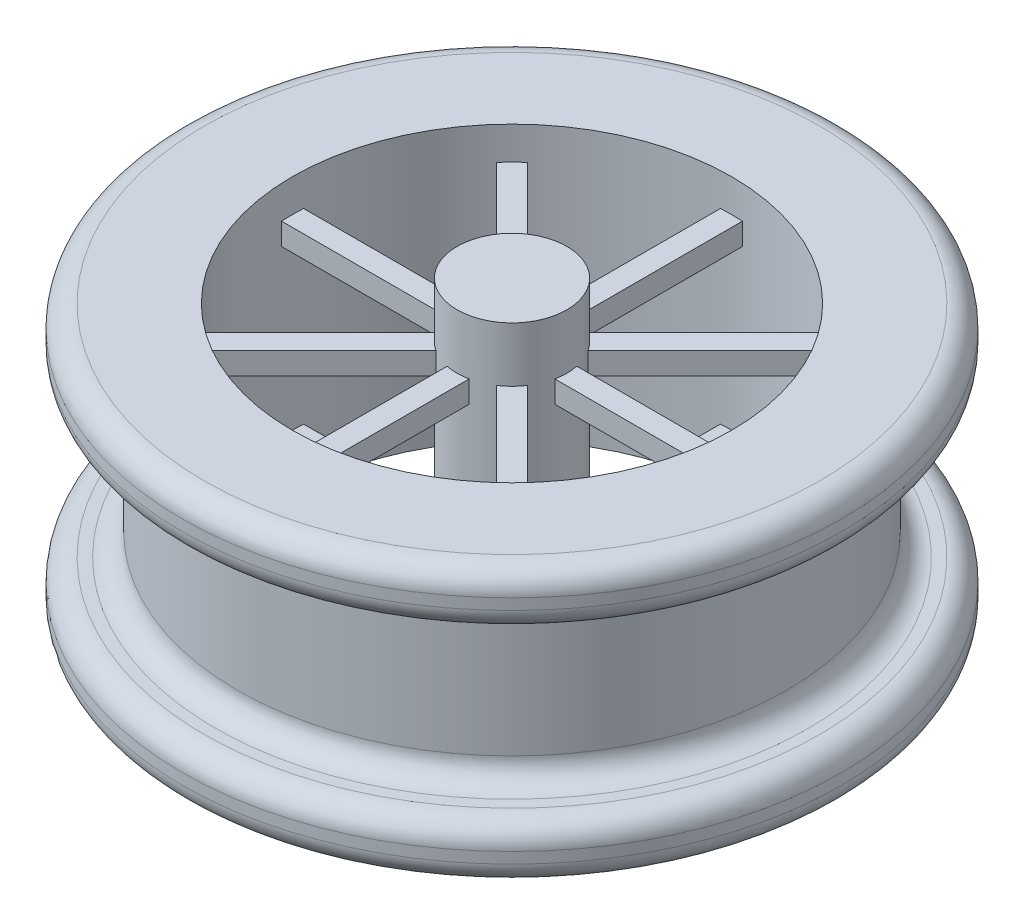
SolidWorks part; units mm, degrees
ref_plane "Front Plane" through (0, 0, 0) normal (0, 0, 1) x (1, 0, 0)
ref_plane "Top Plane" through (0, 0, 0) normal (0, 1, 0) x (1, 0, 0)
ref_plane "Right Plane" through (0, 0, 0) normal (1, 0, 0) x (0, 0, -1)
sketch "Sketch1" plane through (0, 0, 0) normal (0, 1, 0) x (1, 0, 0)
  circle A0 centre (0, 0) radius 63.5
  dimension "D1" = 127
extrude "Boss-Extrude1" add sketch "Sketch1" along normal blind 38.1
sketch "Sketch2" plane through (0, 38.1, 0) normal (0, 1, 0) x (1, 0, 0)
  circle A0 centre (0, 0) radius 76.2
  dimension "D1" = 152.4
extrude "Boss-Extrude2" add sketch "Sketch2" along normal blind 12.7
sketch "Sketch3" plane through (0, 50.8, 0) normal (0, 1, 0) x (1, 0, 0)
  circle A0 centre (0, 0) radius 12.7
  dimension "D1" = 25.4
extrude "Boss-Extrude3" add sketch "Sketch3" along normal blind 5.08
ref_plane "Plane1" through (0, 19.05, 0) normal (0, 1, 0) x (1, 0, 0)
mirror "Mirror1" about plane through (0, 19.05, 0) normal (0, 1, 0) of "Boss-Extrude3", "Boss-Extrude2"
fillet "Fillet1" radius 5.08 6 edges at (0, -12.7, 76.2) (0, 0, 76.2) (0, 0, -63.5) (0, 38.1, 76.2) (0, 38.1, 63.5) (0, 50.8, 76.2)
sketch "Sketch4" plane through (0, -12.7, 0) normal (0, -1, 0) x (1, 0, 0)
  circle A0 centre (0, 0) radius 50.8
  circle A1 centre (0, 0) radius 12.7 construction
  circle A2 centre (0, 0) radius 12.7
  dimension "D1" = 101.6
extrude "Cut-Extrude1" cut sketch "Sketch4" against normal blind 20.32
ref_plane "Plane2" through (0, 19.05, 0) normal (0, -1, 0) x (-1, 0, 0)
mirror "Mirror2" about plane through (0, 19.05, 0) normal (0, -1, 0) of "Cut-Extrude1"
sketch "Sketch5" plane through (0, -17.78, 0) normal (0, -1, 0) x (1, 0, 0)
  circle A0 centre (0, 0) radius 3.81
extrude "Boss-Extrude4" add sketch "Sketch5" along normal blind 10.16
sketch "Sketch6" plane through (0, 0, 0) normal (1, 0, 0) x (0, 0, -1)
  line L1 (2.54, 43.18) -> (-2.54, 43.18)
  line L2 (2.54, 43.18) -> (2.54, 38.1)
  line L3 (2.54, 38.1) -> (-2.54, 38.1)
  line L4 (-2.54, 43.18) -> (-2.54, 38.1)
  line L5 (2.54, 43.18) -> (-2.54, 38.1) construction
  line L6 (2.54, 38.1) -> (-2.54, 43.18) construction
  point P0 (0, 40.64)
  dimension "D1" = 40.64
  dimension "D2" = 5.08
  dimension "D3" = 5.08
extrude "Boss-Extrude5" add sketch "Sketch6" along normal blind 50.8
pattern_circular "CirPattern1" count 8 over 360 about axis through (0, 0, 0) along (0, 1, 0) of "Boss-Extrude5"
mirror "Mirror3" about plane through (0, 19.05, 0) normal (0, -1, 0) of "CirPattern1", "Boss-Extrude5"
sketch "Sketch7" plane through (0, 7.62, 0) normal (0, -1, 0) x (1, 0, 0)
  circle A0 centre (0, 0) radius 12.7 construction
  circle A1 centre (0, 0) radius 50.8
  circle A2 centre (0, 0) radius 50.8
  circle A3 centre (0, 0) radius 12.7
  dimension "D1" = 0
extrude "Cut-Extrude2" cut sketch "Sketch7" against normal blind 22.86
